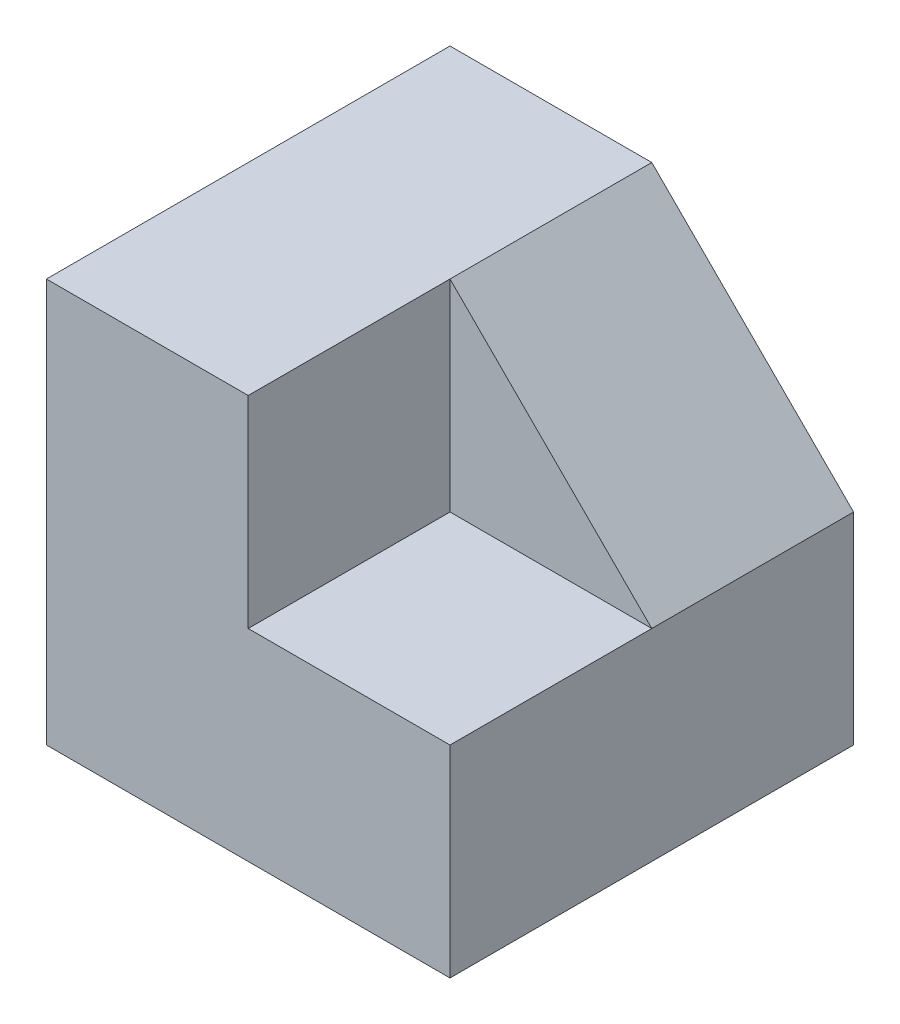
SolidWorks part; units mm, degrees
ref_plane "Alzado" through (0, 0, 0) normal (0, 0, 1) x (1, 0, 0)
ref_plane "Planta" through (0, 0, 0) normal (0, 1, 0) x (1, 0, 0)
ref_plane "Vista lateral" through (0, 0, 0) normal (1, 0, 0) x (0, 0, -1)
sketch "Croquis1" plane through (0, 0, 0) normal (0, 1, 0) x (1, 0, 0)
  line L1 (30, 30) -> (-30, 30)
  line L2 (30, 30) -> (30, -30)
  line L3 (30, -30) -> (-30, -30)
  line L4 (-30, 30) -> (-30, -30)
  line L5 (30, 30) -> (-30, -30) construction
  line L6 (30, -30) -> (-30, 30) construction
  point P0 (0, 0)
  dimension "D1" = 60
  dimension "D2" = 60
extrude "Saliente-Extruir1" add sketch "Croquis1" along normal blind 30 contours L2 L1 L4 L3
sketch "Croquis2" plane through (0, 30, 0) normal (0, 1, 0) x (1, 0, 0)
  line L0 (0, -30) -> (0, 0)
  line L1 (0, 0) -> (30, 0)
  line L4 (-30, -30) -> (30, -30)
  line L5 (30, -30) -> (30, 30)
  line L6 (30, 30) -> (-30, 30)
  line L7 (-30, 30) -> (-30, -30)
  line L8 (-30, -30) -> (0, -30)
  line L9 (30, 0) -> (30, 30)
  line L10 (30, 30) -> (-30, 30)
  line L11 (-30, 30) -> (-30, -30)
  dimension "D2" = 30
  dimension "D3" = 30
  dimension "D1" = 0
extrude "Saliente-Extruir2" add sketch "Croquis2" along normal blind 30 contours L8 L0 L1 L9 L10 L11
chamfer "Chaflán1" distance 30 1 edges at (30, 60, -15)
